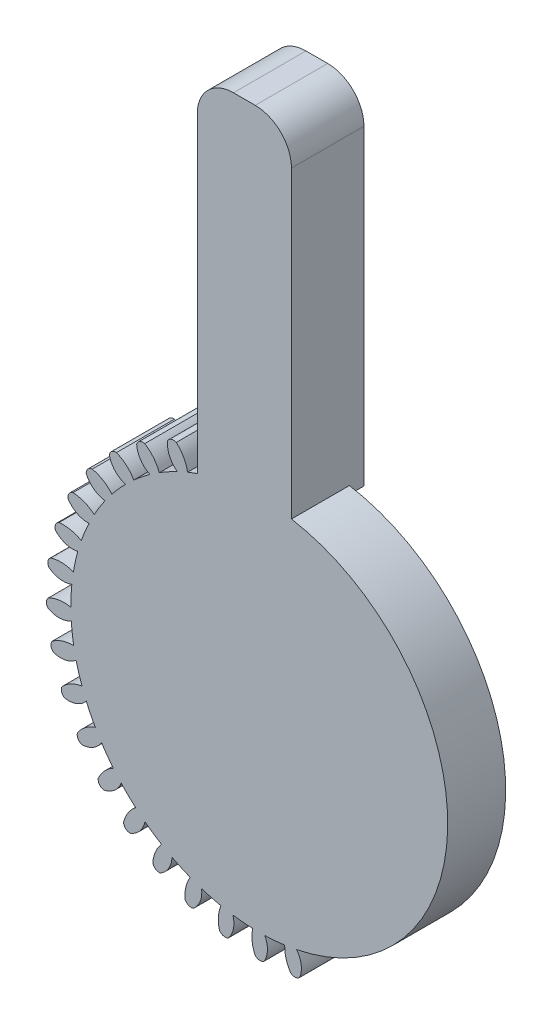
SolidWorks part; units mm, degrees
ref_plane "Front Plane" through (0, 0, 0) normal (0, 0, 1) x (1, 0, 0)
ref_plane "Top Plane" through (0, 0, 0) normal (0, 1, 0) x (1, 0, 0)
ref_plane "Right Plane" through (0, 0, 0) normal (1, 0, 0) x (0, 0, -1)
sketch "Sketch1" plane through (0, 0, 0) normal (0, 0, 1) x (1, 0, 0)
  circle A0 centre (0, 0) radius 13
extrude "Boss-Extrude1" add sketch "Sketch1" along normal blind 4
sketch "Sketch2" plane through (0, 0, 4) normal (0, 0, 1) x (1, 0, 0)
  line L0 (-1.4428, 12.9197) -> (-0.6734, 12.9825)
  arc A0 (-0.6734, 12.9825) -> (-0.9461, 14.5534) centre (-3.0521, 13.3787) ccw
  circle A1 centre (0, 0) radius 13 construction
  arc A2 (-0.9461, 14.5534) -> (-1.5815, 14.5534) centre (-1.2638, 14.2357) ccw
  arc A3 (-1.5815, 14.5534) -> (-1.4428, 12.9197) centre (-0.1322, 13.8537) ccw
extrude "Boss-Extrude2" add sketch "Sketch2" against normal blind 4
pattern_circular "CirPattern1" count 37 over 360 about axis through (-0.0036, 0.0409, 0) along (0, 0, 1) of "Boss-Extrude2"
sketch "Sketch3" plane through (0, 0, 4) normal (0, 0, 1) x (1, 0, 0)
  arc A0 (2.5802, -12.7414) -> (2.9293, 12.6657) centre (0, 0) ccw
  arc A1 (3.0764, -15.1916) -> (3.4926, 15.1014) centre (0, 0) ccw
  arc A2 (2.5802, -12.7414) -> (3.0764, -15.1916) centre (1.6032, -14.2146) cw
  arc A3 (3.4926, 15.1014) -> (2.9293, 12.6657) centre (4.4288, 13.6019) ccw
  dimension "D1" = 2.5
extrude "Cut-Extrude1" cut sketch "Sketch3" against normal blind 6
sketch "Sketch5" plane through (0, 0, 4) normal (0, 0, 1) x (1, 0, 0)
  line L1 (-4.2795, 12.2754) -> (2.2205, 12.2754)
  line L2 (-4.2795, 12.2754) -> (-4.2795, 36.2754)
  line L3 (-4.2795, 36.2754) -> (2.2205, 36.2754)
  line L4 (2.2205, 12.2754) -> (2.2205, 36.2754)
  arc A0 (-3.5992, 12.4918) -> (-4.9469, 12.022) centre (0, 0) ccw construction
  dimension "D1" = 24
  dimension "D2" = 6.5
extrude "Boss-Extrude3" add sketch "Sketch5" against normal blind 5
fillet "Fillet1" radius 2.5 2 edges at (2.2205, 36.2754, 1.5) (-4.2795, 36.2754, 1.5)
